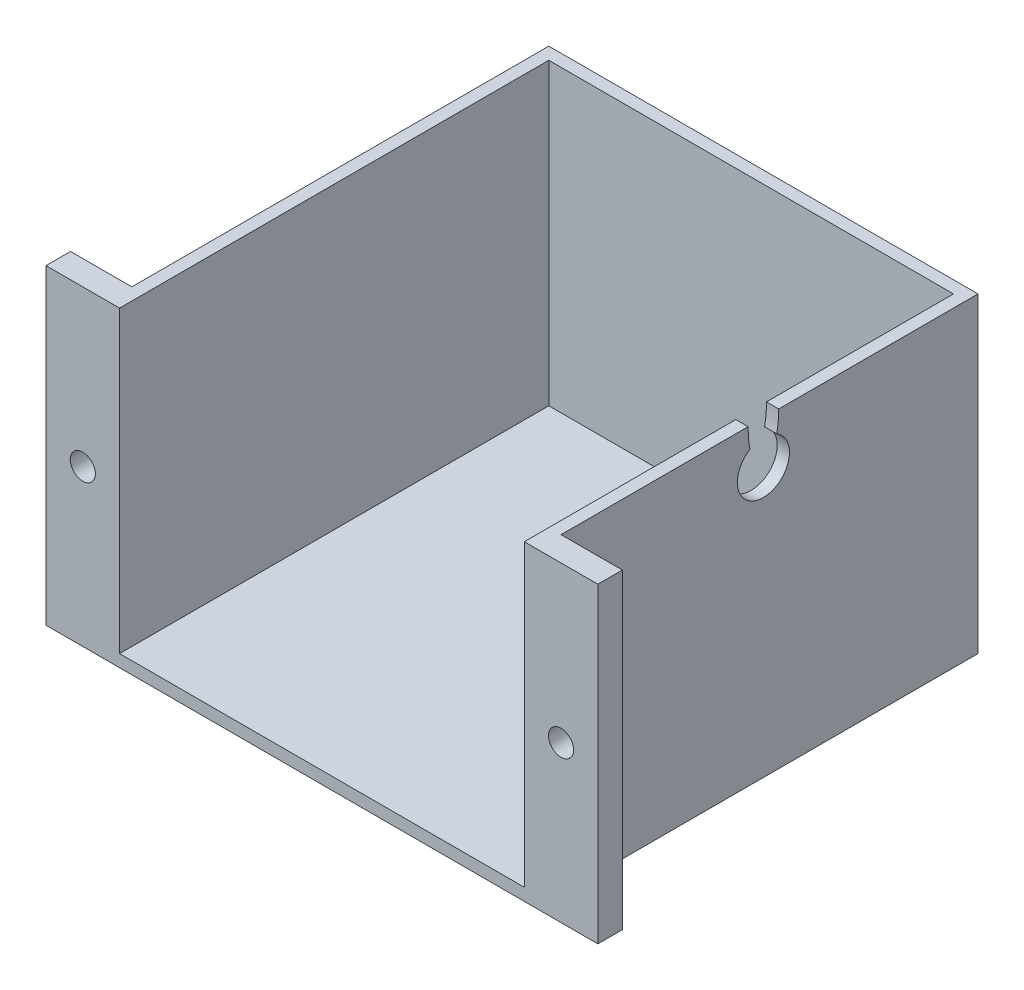
SolidWorks part; units mm, degrees
ref_plane "Front Plane" through (0, 0, 0) normal (0, 0, 1) x (1, 0, 0)
ref_plane "Top Plane" through (0, 0, 0) normal (0, 1, 0) x (1, 0, 0)
ref_plane "Right Plane" through (0, 0, 0) normal (1, 0, 0) x (0, 0, -1)
sketch "Sketch1" plane through (0, 0, 0) normal (0, 1, 0) x (1, 0, 0)
  line L0 (-10, 0) -> (0, 0)
  line L1 (0, 0) -> (0, 68)
  line L2 (0, 68) -> (70, 68)
  line L3 (70, 68) -> (70, 0)
  line L4 (70, 0) -> (80, 0)
  line L5 (80, 0) -> (80, -4)
  line L6 (80, -4) -> (68, -4)
  line L7 (68, -4) -> (68, 66)
  line L8 (68, 66) -> (2, 66)
  line L9 (2, 66) -> (2, -4)
  line L10 (2, -4) -> (-10, -4)
  line L11 (-10, -4) -> (-10, 0)
  dimension "D1" = 4
  dimension "D2" = 2
  dimension "D3" = 2
  dimension "D4" = 2
  dimension "D5" = 70
  dimension "D6" = 10
  dimension "D7" = 70
extrude "Boss-Extrude1" add sketch "Sketch1" along normal blind 50.8
sketch "CableHoleSketch2" plane through (70, 0, 0) normal (1, 0, 0) x (0, 0, -1)
  line L0 (0, 50.8) -> (68, 50.8) construction
  line L2 (30.5, 50.8) -> (35.5, 50.8)
  arc A0 (30.8068, 47.4404) -> (35.1932, 47.4404) centre (33, 43.8) ccw
  ellipse E0 centre (33, 50.8) end of major axis (33, 43.8) minor radius 2.5 (30.5, 50.8) -> (30.8068, 47.4404) ccw
  ellipse E1 centre (33, 50.8) end of major axis (33, 43.8) minor radius 2.5 (35.1932, 47.4404) -> (35.5, 50.8) ccw
  dimension "D4" = 8.5
  dimension "D1" = 35
  dimension "D2" = 5
  dimension "D3" = 7
sketch "BottomCoverSketch3" plane through (0, 0, -66) normal (0, 0, 1) x (1, 0, 0)
  line L0 (2, 0) -> (68, 0) construction
  line L1 (2, 0) -> (68, 0)
  line L2 (2, 0) -> (2, 2)
  line L3 (2, 2) -> (68, 2)
  line L4 (68, 0) -> (68, 2)
  line L5 (68, 50.8) -> (68, 0) construction
  line L6 (2, 50.8) -> (2, 0) construction
extrude "BottomCoverBoss-Extrude2" add sketch "BottomCoverSketch3" along normal blind 70
sketch "MountingHolesSketch4" plane through (0, 0, 4) normal (0, 0, 1) x (1, 0, 0)
  line L0 (68, 50.8) -> (80, 0) construction
  line L1 (-10, 0) -> (2, 50.8) construction
  circle A0 centre (74, 25.4) radius 2.05
  circle A1 centre (-4, 25.4) radius 2.05
  dimension "D1" = 4.1
extrude "MountingHolesCut-Extrude2" cut sketch "MountingHolesSketch4" against normal blind 4
extrude "CableHoleCut-Extrude1" cut sketch "CableHoleSketch2" against normal up to next
equation "\"PowerSwitchCoverWallThickness\"=2"
equation "\"PowerSwitchCoverWidth\"= 70mm"
equation "\"PowerSwitchCoverHeight\"= 50.8mm"
equation "\"PowerSwitchCoverTabWidth\"= 10mm"
equation "\"D1@BottomCoverSketch3\" = \"PowerSwitchCoverWallThickness\""
equation "\"D1@BottomCoverBoss-Extrude2\" = \"PowerSwitchCoverWidth\""
equation "\"PowerSwitchCoverLength\"= 70mm"
equation "\"D7@Sketch1\"=\"PowerSwitchCoverLength\""
equation "\"D5@Sketch1\"=\"PowerSwitchCoverWidth\""
equation "\"D3@Sketch1\"=\"PowerSwitchCoverWallThickness\""
equation "\"D1@Sketch1\"=\"M3HeatInsertHoleDepth\""
equation "\"D4@Sketch1\"=\"PowerSwitchCoverWallThickness\""
equation "\"D6@Sketch1\"=\"PowerSwitchCoverTabWidth\""
equation "\"M3HeatInsertHoleDiameter\"= 4mm + .1mm'Add .1mm for printing"
equation "\"M3HeatInsertHoleDepth\"= 4mm"
equation "\"D1@MountingHolesSketch4\"=\"M3HeatInsertHoleDiameter\""
equation "\"D2@Sketch1\"=\"PowerSwitchCoverWallThickness\""
equation "\"D1@Boss-Extrude1\"=\"PowerSwitchCoverHeight\""
